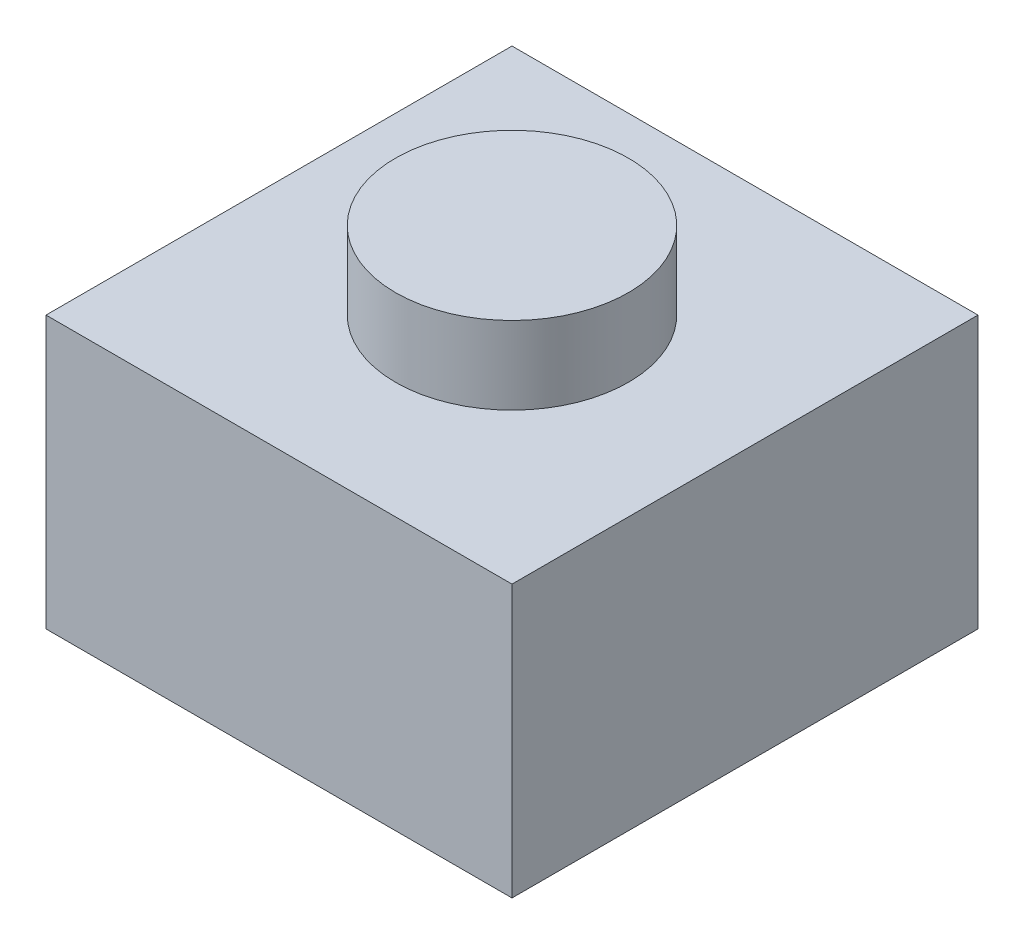
SolidWorks part; units mm, degrees
other "Исправление2"
sketch "Эскиз4" plane through (6, 4.5, 0) normal (0.9437, 0.1201, -0.3083) x (-0.2969, -0.1035, -0.9493)
other "Исправление6"
sketch "Эскиз8"
ref_plane "Спереди" through (0, 0, 0) normal (0, 0, 1) x (1, 0, 0)
ref_plane "Сверху" through (0, 0, 0) normal (0, 1, 0) x (1, 0, 0)
ref_plane "Справа" through (0, 0, 0) normal (1, 0, 0) x (0, 0, -1)
other "Configuration Table"
sketch "Эскиз1" plane through (0, 0, 0) normal (0, 1, 0) x (1, 0, 0)
  line L1 (0, 0) -> (6, 0)
  line L2 (0, 0) -> (0, -6)
  line L3 (0, -6) -> (6, -6)
  line L4 (6, 0) -> (6, -6)
  dimension "D1" = 6
  dimension "D2" = 6
extrude "Бобышка-Вытянуть1" add sketch "Эскиз1" along normal blind 3.5
sketch "Эскиз2" plane through (0, 3.5, 0) normal (0, 1, 0) x (1, 0, 0)
  line L0 (0, 0) -> (0, -6) construction
  line L1 (6, 0) -> (0, 0) construction
  circle A0 centre (3, -3) radius 1.5
  dimension "D1" = 3
  dimension "D3" = 3
  dimension "D2" = 3
extrude "Бобышка-Вытянуть2" add sketch "Эскиз2" along normal blind 1
